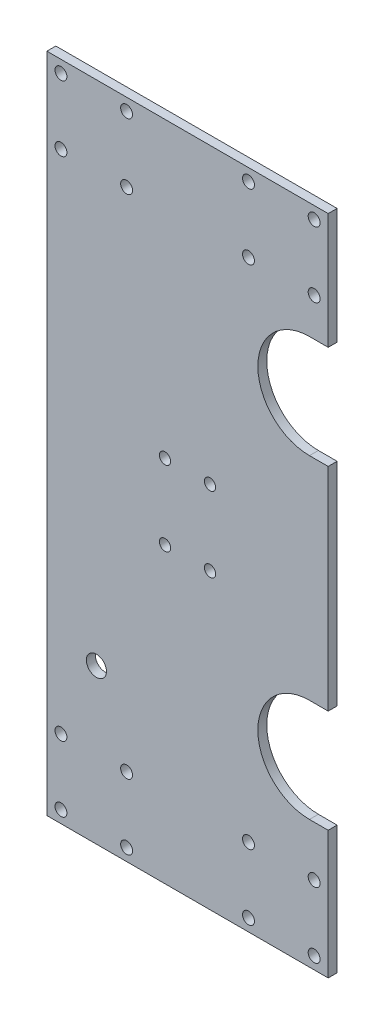
SolidWorks part; units mm, degrees
ref_plane "Alzado" through (0, 0, 0) normal (0, 0, 1) x (1, 0, 0)
ref_plane "Planta" through (0, 0, 0) normal (0, 1, 0) x (1, 0, 0)
ref_plane "Vista lateral" through (0, 0, 0) normal (1, 0, 0) x (0, 0, -1)
sketch "Croquis1" plane through (0, 0, 0) normal (0, 0, 1) x (1, 0, 0)
  line L1 (-75, -176.5) -> (75, -176.5)
  line L2 (-75, -176.5) -> (-75, 176.5)
  line L3 (-75, 176.5) -> (75, 176.5)
  line L4 (75, -176.5) -> (75, 176.5)
  line L5 (-75, -176.5) -> (75, 176.5) construction
  line L6 (-75, 176.5) -> (75, -176.5) construction
  point P0 (0, 0)
  dimension "D1" = 150
  dimension "D2" = 353
extrude "Saliente-Extruir1" add sketch "Croquis1" along normal blind 4.7625
sketch "Croquis2" plane through (0, 0, 4.7625) normal (0, 0, 1) x (1, 0, 0)
  line L0 (75, 176.5) -> (-75, 176.5) construction
  line L1 (75, 176.5) -> (75, -176.5) construction
  line L2 (75, -176.5) -> (-75, -176.5) construction
  line L3 (-75, 176.5) -> (-75, -176.5) construction
  line L4 (75, 0) -> (-75, 0) construction
  line L5 (-67.5, 135) -> (-32.5, 135) construction
  line L6 (-32.5, 135) -> (32.5, 135) construction
  line L7 (32.5, 135) -> (67.5, 135) construction
  line L8 (67.5, 135) -> (67.5, 170) construction
  line L9 (67.5, 170) -> (32.5, 170) construction
  line L10 (32.5, 170) -> (-32.5, 170) construction
  line L11 (-32.5, 170) -> (-67.5, 170) construction
  line L12 (-67.5, 170) -> (-67.5, 135) construction
  line L13 (-32.5, 170) -> (-32.5, 135) construction
  line L14 (32.5, 170) -> (32.5, 135) construction
  line L15 (-67.5, -135) -> (-32.5, -135) construction
  line L16 (-32.5, -135) -> (32.5, -135) construction
  line L17 (32.5, -135) -> (67.5, -135) construction
  line L18 (67.5, -135) -> (67.5, -170) construction
  line L19 (67.5, -170) -> (32.5, -170) construction
  line L20 (32.5, -170) -> (-32.5, -170) construction
  line L21 (-32.5, -170) -> (-67.5, -170) construction
  line L22 (-67.5, -170) -> (-67.5, -135) construction
  line L23 (-32.5, -135) -> (-32.5, -170) construction
  line L24 (32.5, -135) -> (32.5, -170) construction
  line L25 (-67.5, 135) -> (-67.5, -135) construction
  circle A0 centre (-67.5, 170) radius 3.175
  circle A1 centre (-32.5, 170) radius 3.175
  circle A2 centre (-67.5, 135) radius 3.175
  circle A3 centre (-32.5, 135) radius 3.175
  circle A4 centre (32.5, 170) radius 3.175
  circle A5 centre (67.5, 170) radius 3.175
  circle A6 centre (32.5, 135) radius 3.175
  circle A7 centre (67.5, 135) radius 3.175
  circle A8 centre (-67.5, -135) radius 3.175
  circle A9 centre (-32.5, -135) radius 3.175
  circle A10 centre (-67.5, -170) radius 3.175
  circle A11 centre (-32.5, -170) radius 3.175
  circle A12 centre (32.5, -170) radius 3.175
  circle A13 centre (32.5, -135) radius 3.175
  circle A14 centre (67.5, -135) radius 3.175
  circle A15 centre (67.5, -170) radius 3.175
  dimension "D1" = 135
  dimension "D2" = 35
  dimension "D3" = 35
  dimension "D4" = 65
  dimension "D5" = 35
  dimension "D6" = 135
  dimension "D7" = 35
  dimension "D8" = 65
  dimension "D9" = 35
  dimension "D10" = 35
  dimension "D11" = 7.5
  dimension "D12" = 6.5
  dimension "D13" = 7.5
extrude "Cortar-Extruir1" cut sketch "Croquis2" against normal through all
sketch "Croquis3" plane through (0, 0, 0) normal (0, 0, -1) x (-1, 0, 0)
  circle A0 centre (-12, 20) radius 3
  circle A1 centre (12, 20) radius 3
  circle A2 centre (12, -20) radius 3
  circle A3 centre (-12, -20) radius 3
  point P0 (-12, 20)
  point P1 (12, 20)
  point P3 (12, -20)
  point P5 (-12, -20)
  dimension "D1" = 6
extrude "Cortar-Extruir2" cut sketch "Croquis3" against normal up to next
sketch "Croquis4" plane through (0, 0, 4.7625) normal (0, 0, 1) x (1, 0, 0)
  line L0 (-75, 176.5) -> (-75, -176.5) construction
  line L1 (-75, -176.5) -> (75, -176.5) construction
  circle A0 centre (-48.59, -94.11) radius 5
  dimension "D1" = 10
  dimension "D2" = 26.41
  dimension "D3" = 82.39
extrude "Cortar-Extruir3" cut sketch "Croquis4" against normal up to next
sketch "Croquis8" plane through (0, 0, 4.7625) normal (0, 0, 1) x (1, 0, 0)
  line L0 (75, 114.73) -> (65, 114.73)
  line L1 (75, -176.5) -> (75, 176.5) construction
  line L2 (65, 59.73) -> (75, 59.73)
  line L3 (75, 59.73) -> (75, 114.73)
  line L4 (75, 176.5) -> (-75, 176.5) construction
  line L5 (75, -53.27) -> (65, -53.27)
  line L6 (65, -108.27) -> (75, -108.27)
  line L7 (75, -108.27) -> (75, -53.27)
  arc A0 (65, 114.73) -> (65, 59.73) centre (65, 87.23) ccw
  arc A1 (65, -53.27) -> (65, -108.27) centre (65, -80.77) ccw
  dimension "D5" = 10
  dimension "D6" = 257.27
  dimension "D1" = 55
  dimension "D2" = 10
  dimension "D3" = 89.27
  dimension "D4" = 55
extrude "Cortar-Extruir7" cut sketch "Croquis8" against normal up to next
hole_wizard "Taladro roscado 1/2-134" positions "Croquis11" profile "Croquis12" tap size "1/2-13" standard "Ansi Inch"
sketch "Croquis11" plane through (0, 0, 4.7625) normal (0, 0, 1) x (1, 0, 0)
  point P0 (-48.59, -94.11)
sketch "Croquis12" plane through (-48.59, -94.11, 4.7625) normal (1, 0, 0) x (0, -1, 0)
  line L0 (0, 0) -> (0, 38.3895)
  line L1 (0, 38.3895) -> (5.3581, 35.17)
  line L2 (5.3581, 35.17) -> (5.3581, 0)
  line L5 (5.3581, 0) -> (0, 0)
  line L10 (0, 38.3895) -> (-5.3581, 35.17) construction
  line L11 (0, -6.35) -> (0, 107.95) construction
  dimension "Diámetro de perforador para roscar" = 10.7163
  dimension "Profundidad de perforador para roscar" = 35.17
  dimension "Ángulo de perforador" = 118
cosmetic thread "Rosca de taladro1" parameters "D1"=6.35, "D2"=12.7
